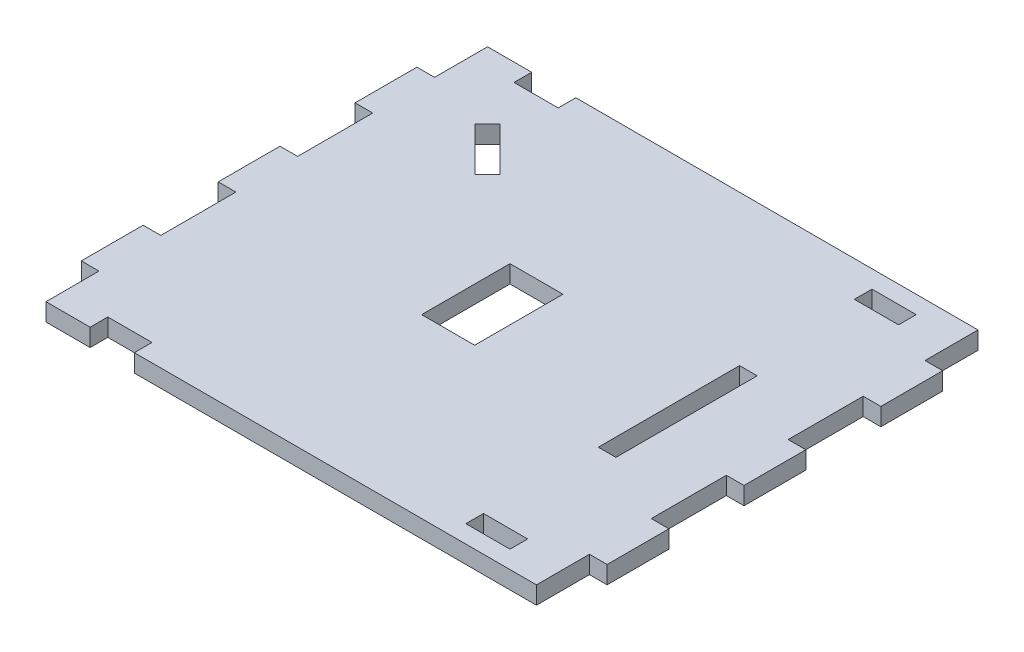
SolidWorks part; units mm, degrees
ref_plane "Front Plane" through (0, 0, 0) normal (0, 0, 1) x (1, 0, 0)
ref_plane "Top Plane" through (0, 0, 0) normal (0, 1, 0) x (1, 0, 0)
ref_plane "Right Plane" through (0, 0, 0) normal (1, 0, 0) x (0, 0, -1)
sketch "Sketch1" plane through (0, 0, 0) normal (0, 1, 0) x (1, 0, 0)
  line L1 (-27.77, 25) -> (27.77, 25)
  line L2 (-27.77, 25) -> (-27.77, -25)
  line L3 (-27.77, -25) -> (27.77, -25)
  line L4 (27.77, 25) -> (27.77, -25)
  line L5 (-27.77, 25) -> (27.77, -25) construction
  line L6 (-27.77, -25) -> (27.77, 25) construction
  line L7 (27.77, -19) -> (29.77, -19)
  line L8 (27.77, -19) -> (27.77, -12)
  line L9 (27.77, -12) -> (29.77, -12)
  line L10 (29.77, -19) -> (29.77, -12)
  line L11 (27.77, -3.5) -> (29.77, -3.5)
  line L12 (27.77, -3.5) -> (27.77, 3.5)
  line L13 (27.77, 3.5) -> (29.77, 3.5)
  line L14 (29.77, -3.5) -> (29.77, 3.5)
  line L15 (27.77, 12) -> (29.77, 12)
  line L16 (27.77, 12) -> (27.77, 19)
  line L17 (27.77, 19) -> (29.77, 19)
  line L18 (29.77, 12) -> (29.77, 19)
  line L19 (17.77, 8) -> (19.77, 8)
  line L20 (17.77, 8) -> (17.77, -8)
  line L21 (17.77, -8) -> (19.77, -8)
  line L22 (19.77, 8) -> (19.77, -8)
  line L23 (-27.77, 19) -> (-29.77, 19)
  line L24 (-27.77, 19) -> (-27.77, 12)
  line L25 (-27.77, 12) -> (-29.77, 12)
  line L26 (-29.77, 19) -> (-29.77, 12)
  line L27 (-27.77, 3.5) -> (-29.77, 3.5)
  line L28 (-27.77, 3.5) -> (-27.77, -3.5)
  line L29 (-27.77, -3.5) -> (-29.77, -3.5)
  line L30 (-29.77, 3.5) -> (-29.77, -3.5)
  line L31 (-27.77, -12) -> (-29.77, -12)
  line L32 (-27.77, -12) -> (-27.77, -19)
  line L33 (-27.77, -19) -> (-29.77, -19)
  line L34 (-29.77, -12) -> (-29.77, -19)
  point P0 (0, 0)
  dimension "D1" = 50
  dimension "D2" = 55.54
  dimension "D3" = 2
  dimension "D4" = 2
  dimension "D5" = 2
  dimension "D6" = 7
  dimension "D7" = 7
  dimension "D8" = 7
  dimension "D9" = 6
  dimension "D10" = 8.5
  dimension "D11" = 8.5
  dimension "D12" = 6
  dimension "D13" = 2
  dimension "D14" = 16
  dimension "D15" = 17
  dimension "D16" = 17
  dimension "D17" = 10
  dimension "D18" = 7
  dimension "D19" = 7
  dimension "D20" = 7
  dimension "D21" = 2
  dimension "D22" = 2
  dimension "D23" = 2
  dimension "D24" = 8.5
  dimension "D25" = 8.5
  dimension "D26" = 6
  dimension "D27" = 6
extrude "Boss-Extrude1" add sketch "Sketch1" along normal blind 2 contours L4 L1 L2 L3 L19 L22 L21 L20 | L11 L14 L13 L4 | L15 L18 L17 L4 | L7 L10 L9 L4 | L27 L30 L29 L2 | L31 L34 L33 L2 | L26 L25 L24 L23
sketch "Sketch3" plane through (0, 2, 0) normal (0, 1, 0) x (1, 0, 0)
  line L0 (-27.77, 25) -> (27.77, 25) construction
  line L1 (17.77, 25) -> (22.77, 25)
  line L2 (17.77, 25) -> (17.77, 23)
  line L3 (17.77, 23) -> (22.77, 23)
  line L4 (22.77, 25) -> (22.77, 23)
  line L5 (27.77, 25) -> (27.77, 19) construction
  line L6 (-27.77, -25) -> (27.77, -25) construction
  line L7 (17.77, -25) -> (22.77, -25)
  line L8 (17.77, -25) -> (17.77, -23)
  line L9 (17.77, -23) -> (22.77, -23)
  line L10 (22.77, -25) -> (22.77, -23)
  line L11 (27.77, -19) -> (27.77, -25) construction
  line L12 (-27.77, 25) -> (27.77, 25) construction
  line L13 (-17.77, 25) -> (-22.77, 25)
  line L14 (-17.77, 25) -> (-17.77, 23)
  line L15 (-17.77, 23) -> (-22.77, 23)
  line L16 (-22.77, 25) -> (-22.77, 23)
  line L17 (-27.77, -25) -> (27.77, -25) construction
  line L18 (-17.77, -25) -> (-22.77, -25)
  line L19 (-17.77, -25) -> (-17.77, -23)
  line L20 (-17.77, -23) -> (-22.77, -23)
  line L21 (-22.77, -25) -> (-22.77, -23)
  line L22 (-27.77, -19) -> (-27.77, -25) construction
  line L23 (-27.77, 25) -> (-27.77, 19) construction
  line L25 (22.77, 23) -> (17.77, 23)
  line L26 (22.77, 23) -> (22.77, 21)
  line L27 (22.77, 21) -> (17.77, 21)
  line L28 (17.77, 23) -> (17.77, 21)
  line L29 (22.77, -23) -> (17.77, -23)
  line L30 (22.77, -23) -> (22.77, -21)
  line L31 (22.77, -21) -> (17.77, -21)
  line L32 (17.77, -23) -> (17.77, -21)
  dimension "D1" = 5
  dimension "D2" = 2
  dimension "D3" = 5
  dimension "D4" = 2
  dimension "D5" = 5
  dimension "D6" = 5
  dimension "D7" = 5
  dimension "D8" = 5
  dimension "D9" = 2
  dimension "D10" = 2
  dimension "D11" = 5
  dimension "D12" = 5
  dimension "D13" = 2
  dimension "D14" = 2
extrude "Cut-Extrude1" cut sketch "Sketch3" against normal blind 2 contours L32 L9 L30 L31 | L3 L28 L27 L26 | L15 L16 L13 L14 | L20 L21 L18 L19
sketch "Sketch4" plane through (0, 2, 0) normal (0, 1, 0) x (1, 0, 0)
  line L0 (-27.77, -25) -> (-22.77, -25) construction
  line L1 (0.77, 5) -> (-5.23, 5)
  line L2 (0.77, 5) -> (0.77, -5)
  line L3 (0.77, -5) -> (-5.23, -5)
  line L4 (-5.23, 5) -> (-5.23, -5)
  line L5 (0.77, 5) -> (-5.23, -5) construction
  line L6 (0.77, -5) -> (-5.23, 5) construction
  line L7 (-27.77, 25) -> (-22.77, 25) construction
  line L9 (17.77, 8) -> (17.77, -8) construction
  point P0 (-2.23, 0)
  dimension "D1" = 10
  dimension "D2" = 6
  dimension "D3" = 20
  dimension "D4" = 20
  dimension "D5" = 17
extrude "Cut-Extrude2" cut sketch "Sketch4" against normal blind 2
sketch "Sketch5" plane through (0, 2, 0) normal (0, 1, 0) x (1, 0, 0)
  line L0 (-26.3558, 25) -> (-4.7002, 3.3444) construction
  line L1 (-19.4969, 18.1411) -> (-14.5471, 13.1913)
  line L2 (-19.4969, 18.1411) -> (-20.9111, 16.7269)
  line L3 (-14.5471, 13.1913) -> (-15.9613, 11.7771)
  line L4 (-20.9111, 16.7269) -> (-15.9613, 11.7771)
  dimension "D1" = 2
  dimension "D2" = 7
  dimension "D3" = 1.4142
  dimension "D4" = 9.7
extrude "Cut-Extrude3" cut sketch "Sketch5" against normal blind 2
